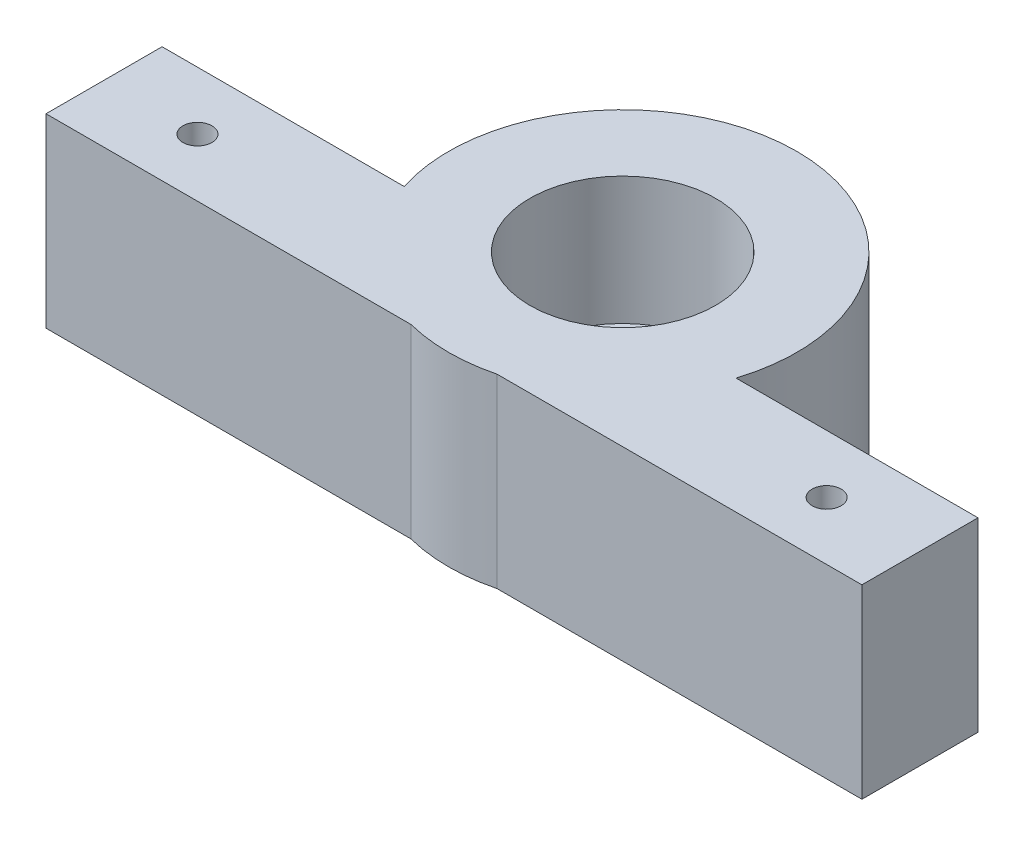
SolidWorks part; units mm, degrees
ref_plane "Front Plane" through (0, 0, 0) normal (0, 0, 1) x (1, 0, 0)
ref_plane "Top Plane" through (0, 0, 0) normal (0, 1, 0) x (1, 0, 0)
ref_plane "Right Plane" through (0, 0, 0) normal (1, 0, 0) x (0, 0, -1)
sketch "Sketch1" plane through (0, 0, 0) normal (0, 1, 0) x (1, 0, 0)
  line L0 (-7.1489, -2.2677) -> (-17.5725, -2.2677)
  line L1 (-17.5725, -2.2677) -> (-17.5725, -7.2677)
  line L3 (-17.5725, -7.2677) -> (-1.8521, -7.2677)
  line L4 (-26.3789, 0) -> (26.3789, 0) construction
  line L5 (-7.2243, -2.2677) -> (-18.1163, -2.2677) construction
  line L6 (7.0711, -7.2677) -> (26.3789, -7.2677) construction
  line L7 (0, 0) -> (0, 16.7972) construction
  line L8 (7.1489, -2.2677) -> (17.5696, -2.2677)
  line L9 (17.5696, -2.2677) -> (17.5696, -7.2677)
  line L10 (17.5696, -7.2677) -> (1.8521, -7.2677)
  arc A0 (-1.8521, -7.2677) -> (1.8521, -7.2677) centre (0, 0) ccw
  arc A1 (7.1489, -2.2677) -> (-7.1489, -2.2677) centre (0, 0) ccw
  circle A3 centre (0, 0) radius 1.875
  circle A5 centre (-13.55, -4.7677) radius 0.625
  circle A6 centre (13.55, -4.7677) radius 0.625
  dimension "D3" = 15
  dimension "D5" = 3.75
  dimension "D6" = 35.1421
  dimension "D2" = 13.55
  dimension "D7" = 1.25
  dimension "D8" = 1.25
  dimension "D10" = 2.5
  dimension "D11" = 13.55
  dimension "D4" = 5
  dimension "D9" = 2.5
extrude "Boss-Extrude1" add sketch "Sketch1" along normal blind 8
sketch "Sketch2" plane through (0, 8, 0) normal (0, 1, 0) x (1, 0, 0)
  circle A0 centre (0, 0) radius 4
  dimension "D1" = 8
extrude "Cut-Extrude1" cut sketch "Sketch2" against normal blind 5.5
